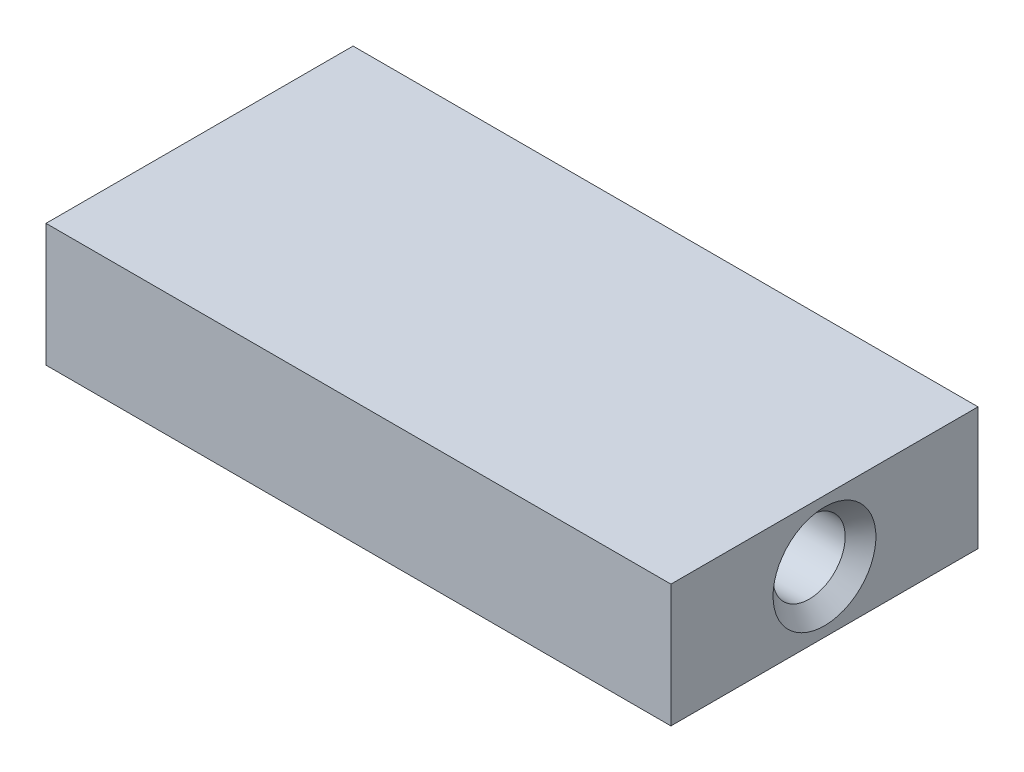
SolidWorks part; units mm, degrees
material "ABS"
ref_plane "Front Plane" through (0, 0, 0) normal (0, 0, 1) x (1, 0, 0)
ref_plane "Top Plane" through (0, 0, 0) normal (0, 1, 0) x (1, 0, 0)
ref_plane "Right Plane" through (0, 0, 0) normal (1, 0, 0) x (0, 0, -1)
sketch "Sketch1" plane through (0, 0, 0) normal (0, 1, 0) x (1, 0, 0)
  line L1 (-20.35, 10) -> (20.35, 10)
  line L2 (-20.35, 10) -> (-20.35, -10)
  line L3 (-20.35, -10) -> (20.35, -10)
  line L4 (20.35, 10) -> (20.35, -10)
  line L5 (-20.35, 10) -> (20.35, -10) construction
  line L6 (-20.35, -10) -> (20.35, 10) construction
  point P0 (0, 0)
  dimension "D1" = 20
  dimension "D2" = 40.7
extrude "Boss-Extrude1" add sketch "Sketch1" along normal blind 8
sketch "Sketch2" plane through (20.35, 0, 0) normal (1, 0, 0) x (0, 0, -1)
  line L0 (0, 8) -> (0, 4) construction
  line L1 (-10, 8) -> (10, 8) construction
  line L2 (0, 4) -> (10, 4) construction
  line L3 (10, 8) -> (10, 0) construction
  circle A0 centre (0, 4) radius 2.35
  dimension "D1" = 4.7
extrude "Cut-Extrude1" cut sketch "Sketch2" against normal blind 10
sketch "Sketch3" plane through (-20.35, 0, 0) normal (-1, 0, 0) x (0, 0, 1)
  line L0 (0, 8) -> (0, 4) construction
  line L1 (-10, 8) -> (10, 8) construction
  line L2 (0, 4) -> (10, 4) construction
  line L3 (10, 8) -> (10, 0) construction
  circle A0 centre (0, 4) radius 2.35
  dimension "D1" = 4.7
extrude "Cut-Extrude2" cut sketch "Sketch3" against normal blind 10
chamfer "Chamfer1" distance 1 angle 45 2 edges at (-20.35, 4, 2.35) (20.35, 4, -2.35)
